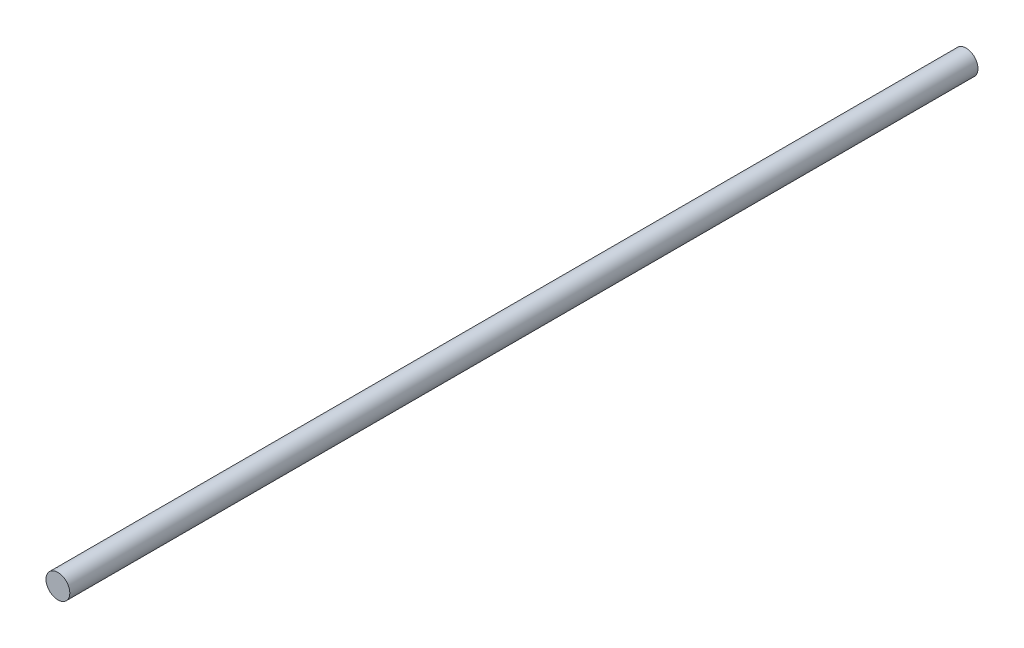
SolidWorks part; units mm, degrees
ref_plane "Front Plane" through (0, 0, 0) normal (0, 0, 1) x (1, 0, 0)
ref_plane "Top Plane" through (0, 0, 0) normal (0, 1, 0) x (1, 0, 0)
ref_plane "Right Plane" through (0, 0, 0) normal (1, 0, 0) x (0, 0, -1)
sketch "Sketch1" plane through (0, 0, 0) normal (0, 0, 1) x (1, 0, 0)
  circle A0 centre (0, 0) radius 5
extrude "Boss-Extrude1" add sketch "Sketch1" along normal blind 381
